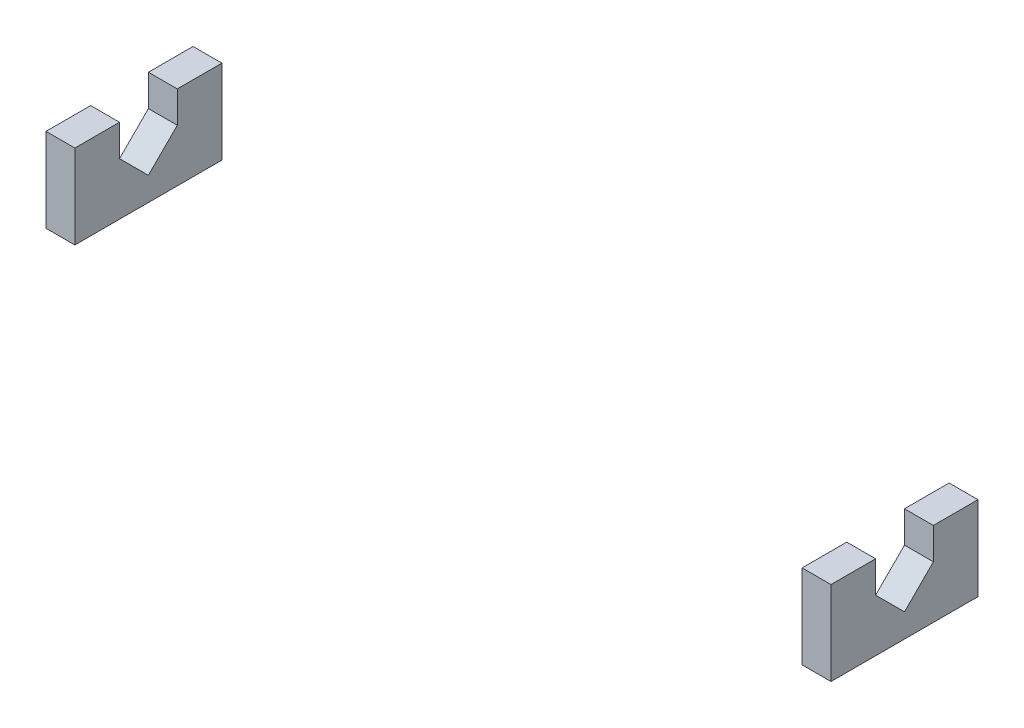
SolidWorks part; units mm, degrees
ref_plane "Front Plane" through (0, 0, 0) normal (0, 0, 1) x (1, 0, 0)
ref_plane "Top Plane" through (0, 0, 0) normal (0, 1, 0) x (1, 0, 0)
ref_plane "Right Plane" through (0, 0, 0) normal (1, 0, 0) x (0, 0, -1)
sketch "Sketch1" plane through (0, 0, 0) normal (1, 0, 0) x (0, -1, 0)
  line L0 (-31.75, 26.9875) -> (-14.2875, 44.45)
  line L1 (0, 0) -> (0, 88.9)
  line L2 (0, 0) -> (-50.8, 0)
  line L3 (-50.8, 0) -> (-50.8, 26.9875)
  line L4 (0, 88.9) -> (-50.8, 88.9)
  line L6 (-50.8, 26.9875) -> (-31.75, 26.9875)
  line L8 (-50.8, 61.9125) -> (-31.75, 61.9125)
  line L9 (-14.2875, 44.45) -> (-31.75, 61.9125)
  line L10 (16.8349, 44.45) -> (-82.107, 44.45) construction
  line L11 (-50.8, 61.9125) -> (-50.8, 88.9)
  point P12 (0, 44.45)
  dimension "D1" = 88.9
  dimension "D2" = 50.8
  dimension "D3" = 19.05
  dimension "D4" = 34.925
extrude "Boss-Extrude1" add sketch "Sketch1" along normal blind 17.4625
pattern_linear "LPattern1" count 2 spacing 457.2 along (1, 0, 0) of bodies 101
